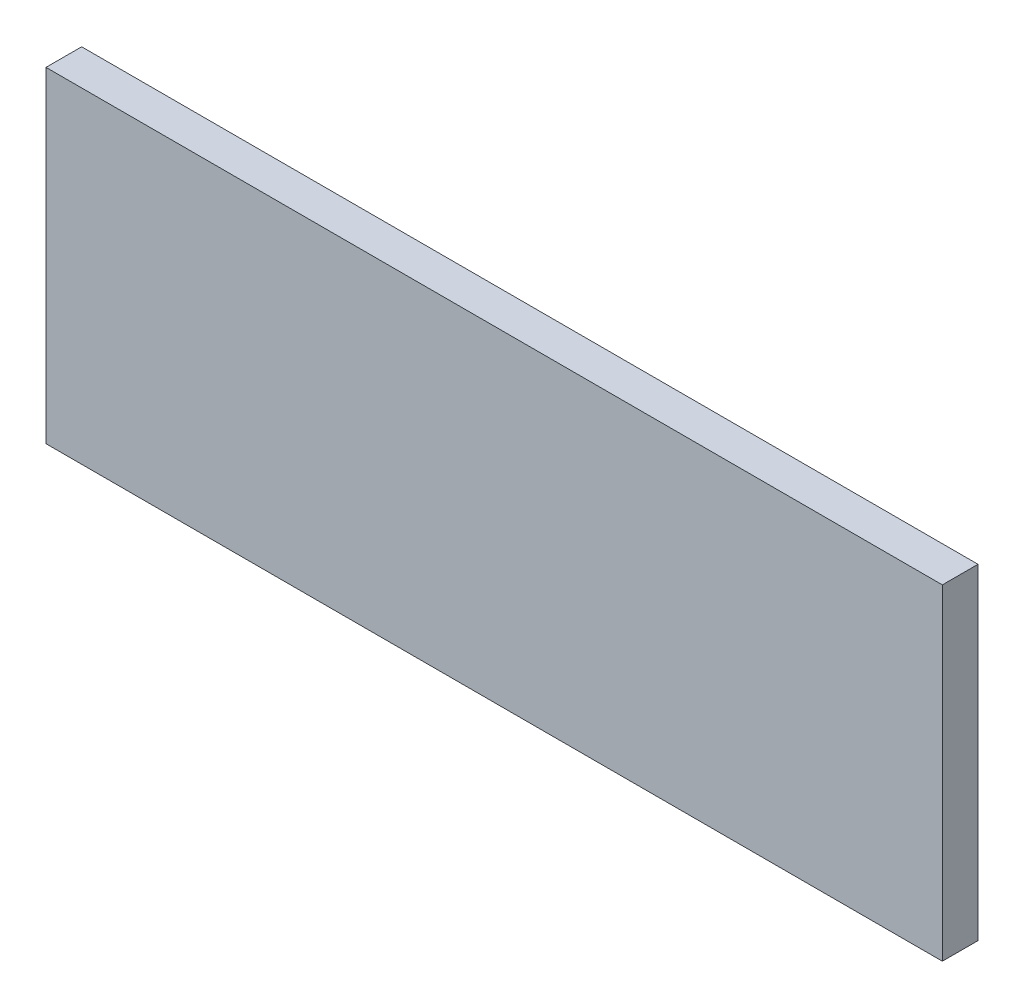
SolidWorks part; units mm, degrees
ref_plane "Front Plane" through (0, 0, 0) normal (0, 0, 1) x (1, 0, 0)
ref_plane "Top Plane" through (0, 0, 0) normal (0, 1, 0) x (1, 0, 0)
ref_plane "Right Plane" through (0, 0, 0) normal (1, 0, 0) x (0, 0, -1)
sketch "Sketch2" plane through (0, 0, 0) normal (0, 0, 1) x (1, 0, 0)
  line L1 (-69.85, -25.4) -> (69.85, -25.4)
  line L2 (-69.85, -25.4) -> (-69.85, 25.4)
  line L3 (-69.85, 25.4) -> (69.85, 25.4)
  line L4 (69.85, -25.4) -> (69.85, 25.4)
  line L5 (-69.85, -25.4) -> (69.85, 25.4) construction
  line L6 (-69.85, 25.4) -> (69.85, -25.4) construction
  point P0 (0, 0)
  dimension "D1" = 50.8
  dimension "D2" = 139.7
extrude "Boss-Extrude1" add sketch "Sketch2" along normal blind 5.5562
